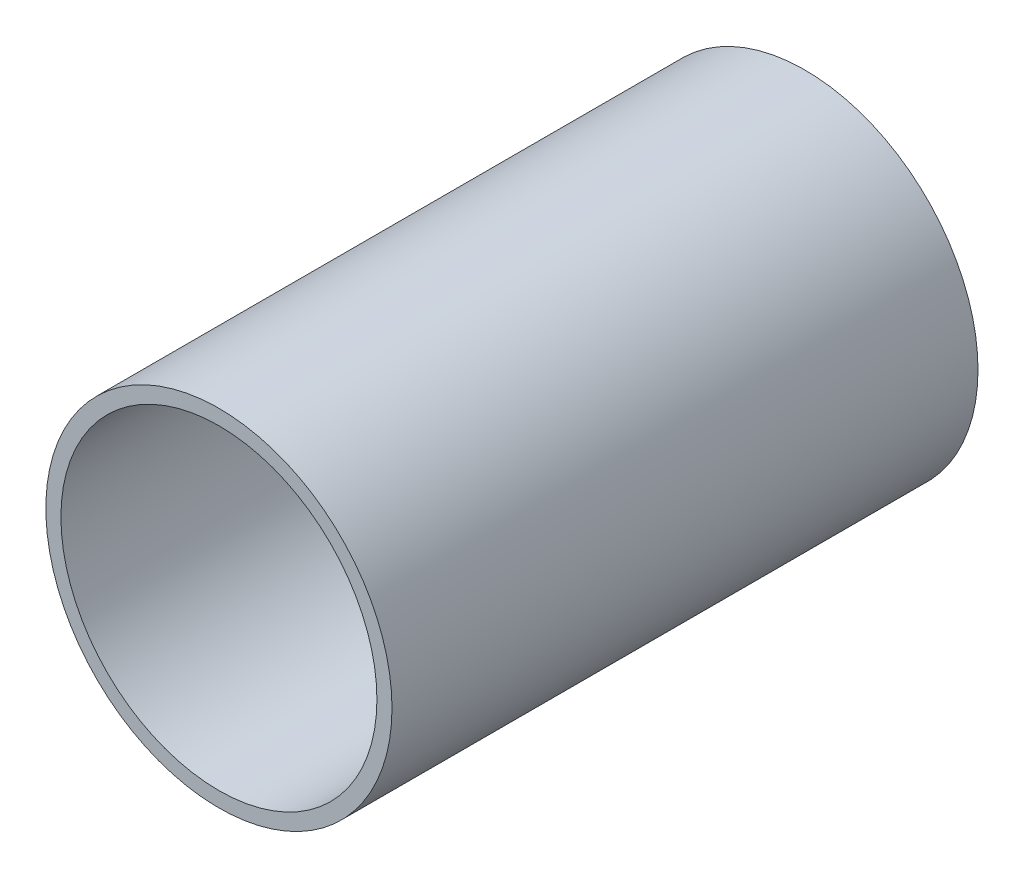
SolidWorks part; units mm, degrees
material "PTFE (general)"
ref_plane "Front Plane" through (0, 0, 0) normal (0, 0, 1) x (1, 0, 0)
ref_plane "Top Plane" through (0, 0, 0) normal (0, 1, 0) x (1, 0, 0)
ref_plane "Right Plane" through (0, 0, 0) normal (1, 0, 0) x (0, 0, -1)
sketch "Sketch1" plane through (0, 0, 0) normal (0, 0, 1) x (0.9999, 0.0151, 0)
  circle A0 centre (-53.9124, 33.1593) radius 10.65
  circle A1 centre (-53.9124, 33.1593) radius 11.666
  dimension "D2" = 23.332
  dimension "D1" = 1.016
extrude "Boss-Extrude1" add sketch "Sketch1" along normal blind 39.5
